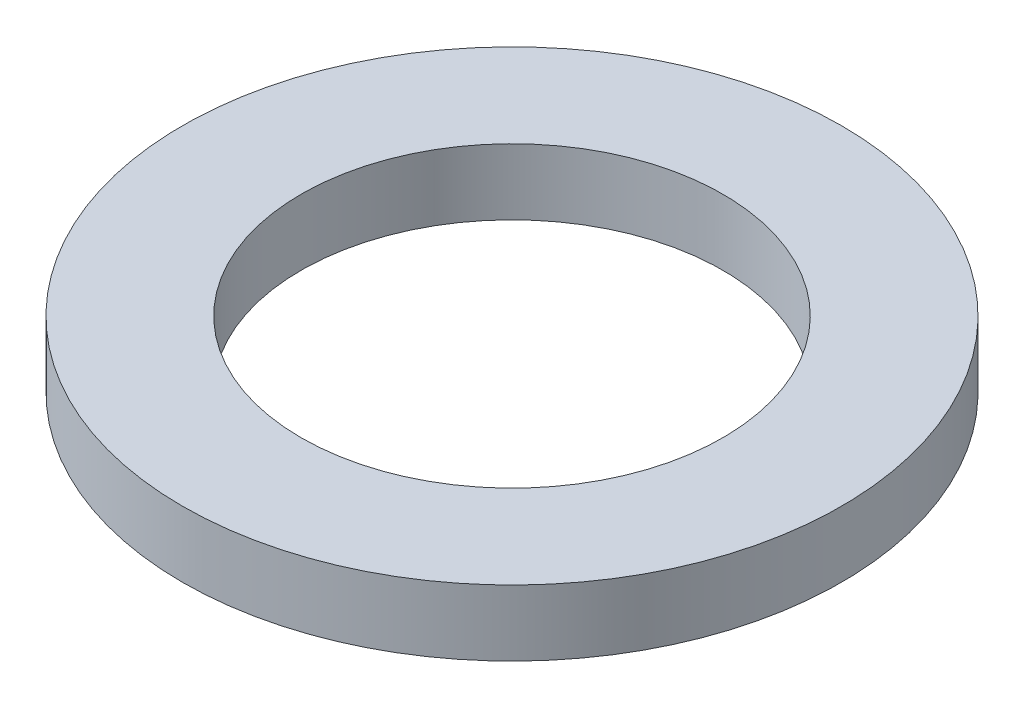
SolidWorks part; units mm, degrees
ref_plane "前视基准面" through (0, 0, 0) normal (0, 0, 1) x (1, 0, 0)
ref_plane "上视基准面" through (0, 0, 0) normal (0, 1, 0) x (1, 0, 0)
ref_plane "右视基准面" through (0, 0, 0) normal (1, 0, 0) x (0, 0, -1)
sketch "草图1" plane through (0, 0, 0) normal (0, 1, 0) x (1, 0, 0)
  circle A0 centre (0, 0) radius 1.6
  circle A1 centre (0, 0) radius 2.5
extrude "凸台-拉伸1" add sketch "草图1" along normal blind 0.5
